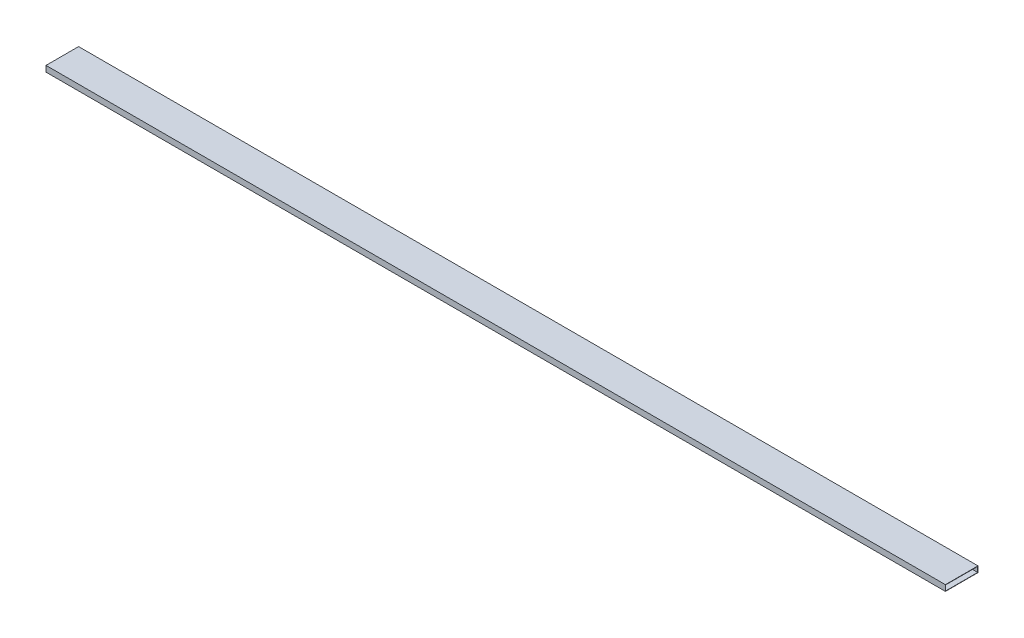
SolidWorks part; units mm, degrees
material "Carbon/Foam Panel"
ref_plane "Front Plane" through (0, 0, 0) normal (0, 0, 1) x (1, 0, 0)
ref_plane "Top Plane" through (0, 0, 0) normal (0, 1, 0) x (1, 0, 0)
ref_plane "Right Plane" through (0, 0, 0) normal (1, 0, 0) x (0, 0, -1)
sketch "Sketch2" plane through (0, 0, 0) normal (1, 0, 0) x (0, 0, -1)
  line L15 (0.6096, -5.715) -> (0.6096, 5.715)
  line L16 (-62.8904, -5.715) -> (0.6096, -5.715)
  line L17 (-62.8904, 5.715) -> (-62.8904, -5.715)
  line L18 (0.6096, 5.715) -> (-62.8904, 5.715)
  line L19 (0.6096, -5.715) -> (0.6096, 5.715)
  line L20 (-62.8904, -5.715) -> (0.6096, -5.715)
  line L21 (-62.8904, 5.715) -> (-62.8904, -5.715)
  line L22 (0.6096, 5.715) -> (-62.8904, 5.715)
  line L23 (-62.2808, -5.1054) -> (0, -5.1054)
  line L24 (0, -5.1054) -> (0, 5.1054)
  line L25 (0, 5.1054) -> (-62.2808, 5.1054)
  line L26 (-62.2808, 5.1054) -> (-62.2808, -5.1054)
  line L27 (-62.2808, -5.1054) -> (0, -5.1054)
  line L28 (0, -5.1054) -> (0, 5.1054)
  line L29 (0, 5.1054) -> (-62.2808, 5.1054)
  line L30 (-62.2808, 5.1054) -> (-62.2808, -5.1054)
  dimension "D1" = 0.6096
  dimension "D2" = 0
extrude "Boss-Extrude1" add sketch "Sketch2" against normal up to vertex (1752.6 mm away)
equation "\"D1@Sketch2\"=3*0.008"
